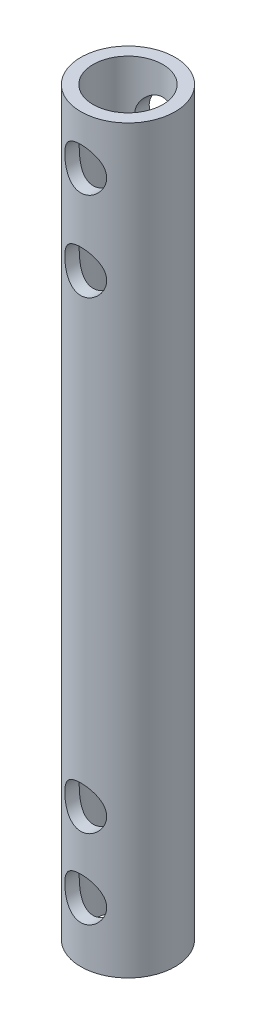
SolidWorks part; units mm, degrees
ref_plane "Front" through (0, 0, 0) normal (0, 0, 1) x (1, 0, 0)
ref_plane "Top" through (0, 0, 0) normal (0, 1, 0) x (1, 0, 0)
ref_plane "Right" through (0, 0, 0) normal (1, 0, 0) x (0, 0, -1)
sketch "Sketch1" plane through (0, 0, 0) normal (0, 1, 0) x (1, 0, 0)
  circle A0 centre (0, 0) radius 9.55
  circle A1 centre (0, 0) radius 7.05
  dimension "D1" = 19.1
  dimension "D2" = 2.5
extrude "Boss-Extrude1" add sketch "Sketch1" along normal blind 150
sketch "Sketch2" plane through (0, 0, 0) normal (0, 0, 1) x (1, 0, 0)
  line L0 (9.55, 150) -> (-9.55, 150) construction
  line L1 (9.55, 150) -> (-9.55, 150) construction
  circle A0 centre (0, 12) radius 4.25
  circle A1 centre (0, 28) radius 4.25
  circle A2 centre (0, 122) radius 4.25
  circle A3 centre (0, 140) radius 4.25
  dimension "D1" = 8.5
  dimension "D2" = 12
  dimension "D4" = 8.5
  dimension "D3" = 16
  dimension "D5" = 18
  dimension "D6" = 10
extrude "Cut-Extrude1" cut sketch "Sketch2" against normal through all both and the other way through all
